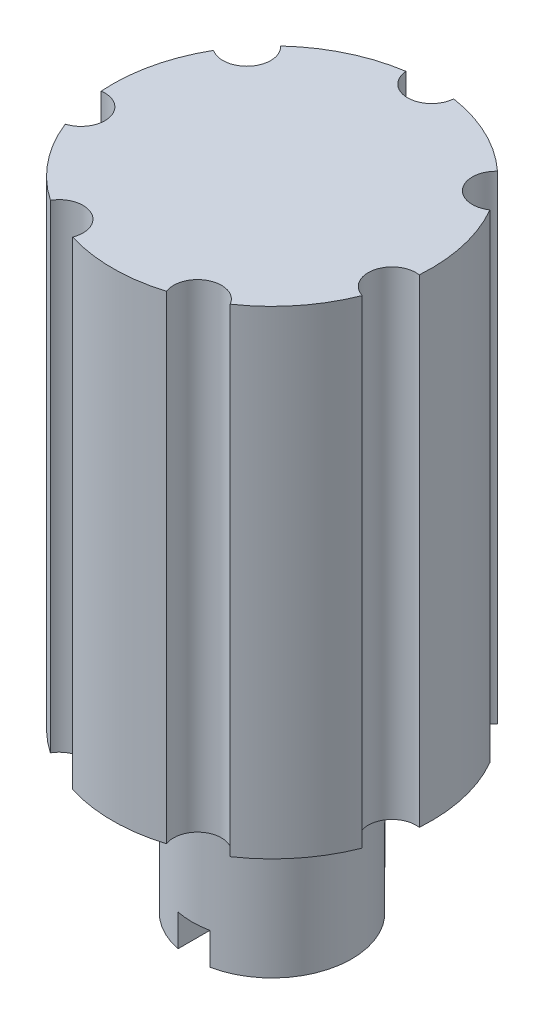
SolidWorks part; units mm, degrees
ref_plane "Front Plane" through (0, 0, 0) normal (0, 0, 1) x (1, 0, 0)
ref_plane "Top Plane" through (0, 0, 0) normal (0, 1, 0) x (1, 0, 0)
ref_plane "Right Plane" through (0, 0, 0) normal (1, 0, 0) x (0, 0, -1)
sketch "Sketch2" plane through (0, 0, 0) normal (0, 1, 0) x (1, 0, 0)
  circle A0 centre (0, 0) radius 2.5
  dimension "D1" = 5
extrude "Boss-Extrude1" add sketch "Sketch2" along normal blind 5
sketch "Sketch3" plane through (0, 5, 0) normal (0, 1, 0) x (1, 0, 0)
  circle A0 centre (0, 0) radius 5
  dimension "D1" = 10
extrude "Boss-Extrude2" add sketch "Sketch3" along normal blind 15
sketch "Sketch4" plane through (0, 20, 0) normal (0, 1, 0) x (1, 0, 0)
  circle A0 centre (0, 5) radius 0.75
  circle A1 centre (0, 0) radius 5 construction
  circle A2 centre (3.9092, 3.1174) radius 0.75
  circle A3 centre (4.8746, -1.1126) radius 0.75
  circle A4 centre (2.1694, -4.5048) radius 0.75
  circle A5 centre (-2.1694, -4.5048) radius 0.75
  circle A6 centre (-4.8746, -1.1126) radius 0.75
  circle A7 centre (-3.9092, 3.1174) radius 0.75
  point P19 (0, 0)
  dimension "D1" = 1.5
extrude "Cut-Extrude1" cut sketch "Sketch4" against normal up to surface (15 mm away) up to face at (0, 5, 2.5)
sketch "Sketch5" plane through (0, 0, 0) normal (0, -1, 0) x (1, 0, 0)
  circle A0 centre (0, 0) radius 1.25
  dimension "D1" = 2.5
extrude "Cut-Extrude2" cut sketch "Sketch5" against normal blind 1
sketch "Sketch6" plane through (0, 0, 0) normal (0, -1, 0) x (1, 0, 0)
  line L0 (0, 0) -> (0, 1.0387) construction
  line L1 (0, 1.25) -> (0, 2.5) construction
  line L3 (-0.5, 2.4495) -> (-0.5, 1.1456)
  line L5 (0.5, 2.4495) -> (0.5, 1.1456)
  circle A1 centre (0, 0) radius 2.5 construction
  circle A2 centre (0, 0) radius 2.5 construction
  arc A3 (0.5, 2.4495) -> (-0.5, 2.4495) centre (0, 0) ccw
  arc A4 (0.5, 1.1456) -> (-0.5, 1.1456) centre (0, 0) ccw
extrude "Cut-Extrude3" cut sketch "Sketch6" against normal up to surface (1 mm away) up to face at (0, 1, -1.25)
